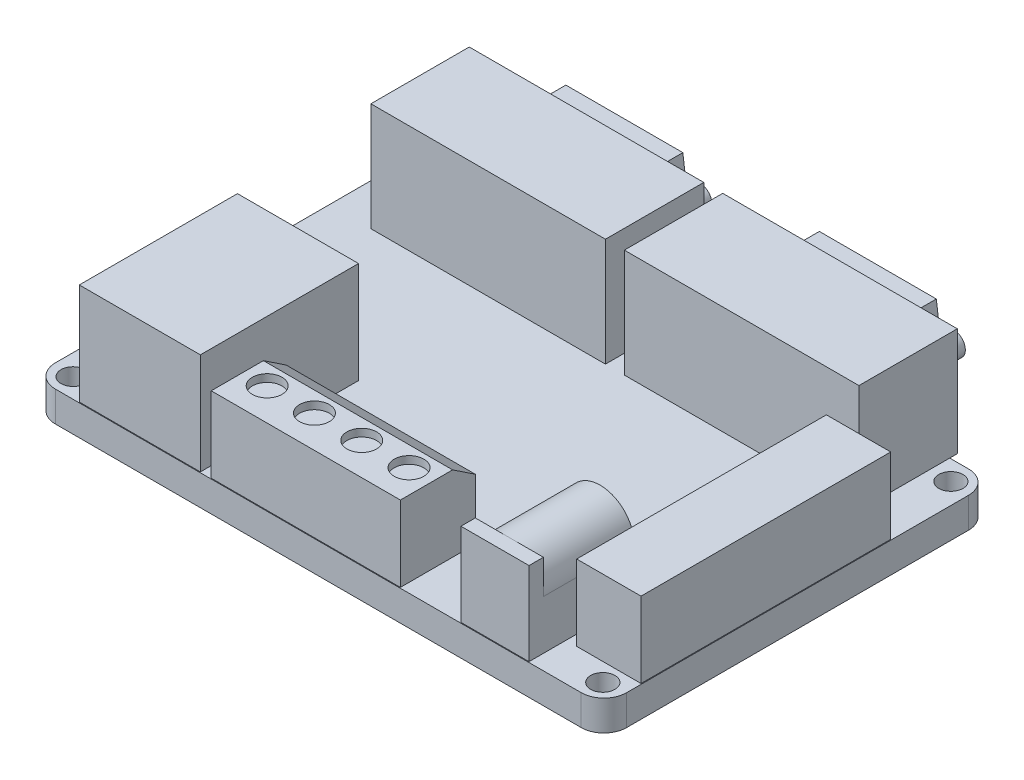
SolidWorks part; units mm, degrees
ref_plane "前视基准面" through (0, 0, 0) normal (0, 0, 1) x (1, 0, 0)
ref_plane "上视基准面" through (0, 0, 0) normal (0, 1, 0) x (1, 0, 0)
ref_plane "右视基准面" through (0, 0, 0) normal (1, 0, 0) x (0, 0, -1)
sketch "草图1" plane through (0, 0, 0) normal (0, 1, 0) x (1, 0, 0)
  line L1 (37.75, -25.6) -> (-37.75, -25.6)
  line L2 (37.75, -25.6) -> (37.75, 25.6)
  line L3 (37.75, 25.6) -> (-37.75, 25.6)
  line L4 (-37.75, -25.6) -> (-37.75, 25.6)
  line L5 (37.75, -25.6) -> (-37.75, 25.6) construction
  line L6 (37.75, 25.6) -> (-37.75, -25.6) construction
  point P0 (0, 0)
  dimension "D1" = 75.5
  dimension "D2" = 51.2
extrude "凸台-拉伸1" add sketch "草图1" along normal blind 4
hole_wizard "M3 间隙孔1" positions "草图2" profile "草图3" hole size "M3" standard "GB" end condition up to next
sketch "草图2" plane through (0, 4, 0) normal (0, 1, 0) x (1, 0, 0)
  line L0 (0, 0) -> (0, 17.2841) construction
  line L2 (0, 0) -> (18.1664, 0) construction
  point P0 (-35, 23)
  point P2 (35, 23)
  point P4 (-35, -23)
  point P6 (35, -23)
  dimension "D1" = 70
  dimension "D2" = 46
sketch "草图3" plane through (-35, 4, -23) normal (1, 0, 0) x (0, 0, 1)
  line L0 (0, 0) -> (0, 4)
  line L1 (0, 4) -> (1.6, 4)
  line L2 (1.6, 4) -> (1.6, 0)
  line L5 (1.6, 0) -> (0, 0)
  line L11 (0, -6.35) -> (0, 107.95) construction
  dimension "通孔孔直径" = 3.2
  dimension "通孔孔深度" = 4
fillet "圆角1" radius 3 4 edges at (-37.75, 2, 25.6) (37.75, 2, 25.6) (37.75, 2, -25.6) (-37.75, 2, -25.6)
sketch "草图4" plane through (0, 0, 25.6) normal (0, 0, 1) x (1, 0, 0)
  line L0 (-34.75, 4) -> (34.75, 4) construction
  line L1 (18.75, 4) -> (27.75, 4)
  line L2 (18.75, 4) -> (18.75, 15)
  line L3 (18.75, 15) -> (27.75, 15)
  line L4 (27.75, 4) -> (27.75, 15)
  line L5 (37.75, 4) -> (37.75, 0) construction
  dimension "D1" = 9
  dimension "D2" = 11
  dimension "D3" = 10
extrude "凸台-拉伸2" add sketch "草图4" against normal blind 14
sketch "草图5" plane through (0, 0, 11.6) normal (0, 0, -1) x (-1, 0, 0)
  line L0 (-27.75, 4) -> (-27.75, 15) construction
  line L1 (-18.75, 15) -> (-18.75, 4) construction
  line L2 (-27.75, 15) -> (-18.75, 15) construction
  line L3 (-27.75, 10.5) -> (-28.75, 10.5)
  line L4 (-28.75, 10.5) -> (-28.75, 16)
  line L5 (-28.75, 16) -> (-17.75, 16)
  line L6 (-17.75, 16) -> (-17.75, 10.5)
  line L7 (-17.75, 10.5) -> (-18.75, 10.5)
  arc A0 (-18.75, 10.5) -> (-27.75, 10.5) centre (-23.25, 10.5) ccw
  dimension "D1" = 1
  dimension "D2" = 1
  dimension "D3" = 1
extrude "切除-拉伸1" cut sketch "草图5" against normal blind 12
sketch "草图6" plane through (0, 4, 0) normal (0, 1, 0) x (1, 0, 0)
  line L0 (-34.75, -25.6) -> (18.75, -25.6) construction
  line L1 (-14.25, -25.6) -> (10.75, -25.6)
  line L2 (-14.25, -25.6) -> (-14.25, -15.6)
  line L3 (-14.25, -15.6) -> (10.75, -15.6)
  line L4 (10.75, -25.6) -> (10.75, -15.6)
  line L5 (18.75, -11.6) -> (18.75, -25.6) construction
  dimension "D1" = 10
  dimension "D2" = 25
  dimension "D3" = 8
extrude "凸台-拉伸3" add sketch "草图6" along normal blind 10
sketch "草图7" plane through (0, 14, 0) normal (0, 1, 0) x (1, 0, 0)
  line L0 (-1.75, -15.6) -> (-1.75, -25.6) construction
  line L1 (10.75, -15.6) -> (-14.25, -15.6) construction
  line L2 (-14.25, -25.6) -> (10.75, -25.6) construction
  line L3 (-1.75, -15.6) -> (-14.25, -15.6) construction
  line L4 (-8, -15.6) -> (-8, -25.6) construction
  line L5 (-8, -25.6) -> (-14.25, -25.6) construction
  circle A0 centre (-11.125, -21.2305) radius 1.963
  circle A1 centre (-4.875, -21.2305) radius 1.963
  circle A2 centre (7.625, -21.2305) radius 1.963
  circle A3 centre (1.375, -21.2305) radius 1.963
  point P19 (-11.125, -25.6)
extrude "切除-拉伸2" cut sketch "草图7" against normal blind 1
chamfer "倒角1" distance 2 distance2 3 1 edges at (-1.75, 14, 15.6)
sketch "草图8" plane through (0, 4, 0) normal (0, 1, 0) x (1, 0, 0)
  line L0 (37.75, -22.6) -> (37.75, 22.6) construction
  line L1 (37.75, 12.4) -> (29.15, 12.4)
  line L2 (37.75, 12.4) -> (37.75, -20.6)
  line L3 (37.75, -20.6) -> (29.15, -20.6)
  line L4 (29.15, 12.4) -> (29.15, -20.6)
  line L5 (27.75, -25.6) -> (34.75, -25.6) construction
  dimension "D1" = 5
  dimension "D2" = 8.6
  dimension "D3" = 33
extrude "凸台-拉伸4" add sketch "草图8" along normal blind 10
sketch "草图9" plane through (0, 4, 0) normal (0, 1, 0) x (1, 0, 0)
  line L0 (0, 0) -> (0, 35.6203) construction
  line L1 (-32.25, 31.6) -> (-1.25, 31.6)
  line L2 (-32.25, 31.6) -> (-32.25, 13.6)
  line L3 (-32.25, 13.6) -> (-1.25, 13.6)
  line L4 (-1.25, 31.6) -> (-1.25, 13.6)
  line L5 (1.25, 31.6) -> (1.25, 13.6)
  line L6 (32.25, 13.6) -> (1.25, 13.6)
  line L7 (32.25, 31.6) -> (32.25, 13.6)
  line L8 (32.25, 31.6) -> (1.25, 31.6)
  line L9 (34.75, 25.6) -> (-34.75, 25.6) construction
  dimension "D1" = 6
  dimension "D2" = 2.5
  dimension "D3" = 12
  dimension "D4" = 31
extrude "凸台-拉伸5" add sketch "草图9" along normal blind 14.3
sketch "草图10" plane through (0, 0, -31.6) normal (0, 0, -1) x (-1, 0, 0)
  line L0 (-16.75, 18.3) -> (-16.75, 4) construction
  line L1 (-32.25, 18.3) -> (-1.25, 18.3) construction
  line L2 (-32.25, 4) -> (-1.25, 4) construction
  line L3 (-9.0203, 15.3252) -> (-24.4797, 15.3252)
  line L4 (-24.4797, 15.3252) -> (-25.4046, 8.1776)
  line L5 (-9.0203, 15.3252) -> (-8.0954, 8.1776)
  line L6 (-25.4046, 8.1776) -> (-8.0954, 8.1776)
  line L7 (0, 0) -> (0, 21.9538) construction
  line L8 (-32.25, 18.3) -> (-1.25, 18.3)
  line L9 (-32.25, 18.3) -> (-32.25, 4)
  line L10 (-32.25, 4) -> (-1.25, 4)
  line L11 (-1.25, 18.3) -> (-1.25, 4)
  line L12 (-32.25, 18.3) -> (-32.25, 4)
  line L13 (-1.25, 18.3) -> (-1.25, 4)
  line L14 (-24.4797, 15.3252) -> (-25.4046, 8.1776)
  line L15 (-9.0203, 15.3252) -> (-8.0954, 8.1776)
  line L16 (16.75, 18.3) -> (16.75, 4) construction
  line L17 (9.0203, 15.3252) -> (8.0954, 8.1776)
  line L18 (24.4797, 15.3252) -> (25.4046, 8.1776)
  line L19 (1.25, 18.3) -> (1.25, 4)
  line L20 (32.25, 18.3) -> (32.25, 4)
  line L21 (1.25, 18.3) -> (1.25, 4)
  line L22 (32.25, 4) -> (1.25, 4)
  line L23 (32.25, 18.3) -> (32.25, 4)
  line L24 (32.25, 18.3) -> (1.25, 18.3)
  line L25 (25.4046, 8.1776) -> (8.0954, 8.1776)
  line L26 (9.0203, 15.3252) -> (8.0954, 8.1776)
  line L27 (24.4797, 15.3252) -> (25.4046, 8.1776)
  line L28 (9.0203, 15.3252) -> (24.4797, 15.3252)
  circle A0 centre (-26.7699, 11.4091) radius 1.5422
  circle A1 centre (-6.7301, 11.4091) radius 1.5422
  circle A2 centre (-26.7699, 11.4091) radius 1.5422
  circle A3 centre (-6.7301, 11.4091) radius 1.5422
  circle A4 centre (6.7301, 11.4091) radius 1.5422
  circle A5 centre (26.7699, 11.4091) radius 1.5422
  circle A6 centre (6.7301, 11.4091) radius 1.5422
  circle A7 centre (26.7699, 11.4091) radius 1.5422
  point P9 (-16.75, 15.3252)
  point P11 (-16.75, 8.1776)
  point P43 (16.75, 8.1776)
  point P44 (16.75, 15.3252)
  line M2 (-32.25, 4) -> (-1.25, 4)
  line M3 (-1.25, 4) -> (-1.25, 18.3)
  line M4 (-1.25, 18.3) -> (-32.25, 18.3)
  line M5 (-32.25, 18.3) -> (-32.25, 4)
extrude "切除-拉伸3" cut sketch "草图10" against normal blind 5 contours L6 L4 L3 L5 A0 A1 M5 M2 M3 M4 | L20 L24 L19 L22 L17 L28 L18 L25 A4 A5
sketch "草图11" plane through (0, 4, 0) normal (0, 1, 0) x (1, 0, 0)
  line L0 (-34.75, -25.6) -> (-14.25, -25.6) construction
  line L1 (-31.6832, -25.6) -> (-15.6832, -25.6)
  line L2 (-31.6832, -25.6) -> (-31.6832, -4.6)
  line L3 (-31.6832, -4.6) -> (-15.6832, -4.6)
  line L4 (-15.6832, -25.6) -> (-15.6832, -4.6)
  dimension "D1" = 16
  dimension "D2" = 21
extrude "凸台-拉伸6" add sketch "草图11" along normal blind 13.4
sketch "草图12" plane through (0, 0, 25.6) normal (0, 0, 1) x (1, 0, 0)
  line L1 (-31.6832, 17.4) -> (27.75, 17.4)
  line L2 (-31.6832, 17.4) -> (-31.6832, 4)
  line L3 (-31.6832, 4) -> (27.75, 4)
  line L4 (27.75, 17.4) -> (27.75, 4)
extrude "切除-拉伸4" cut sketch "草图12" against normal blind 0.1
sketch "草图13" plane through (37.75, 0, 0) normal (1, 0, 0) x (0, 0, -1)
  line L0 (13.6, 4) -> (25.6, 4) construction
  line L1 (-20.6, 14) -> (12.4, 14)
  line L2 (-20.6, 14) -> (-20.6, 4)
  line L3 (-20.6, 4) -> (12.4, 4)
  line L4 (12.4, 14) -> (12.4, 4)
  line L5 (12.4, 14) -> (12.4, 4) construction
extrude "切除-拉伸5" cut sketch "草图13" against normal blind 0.1
